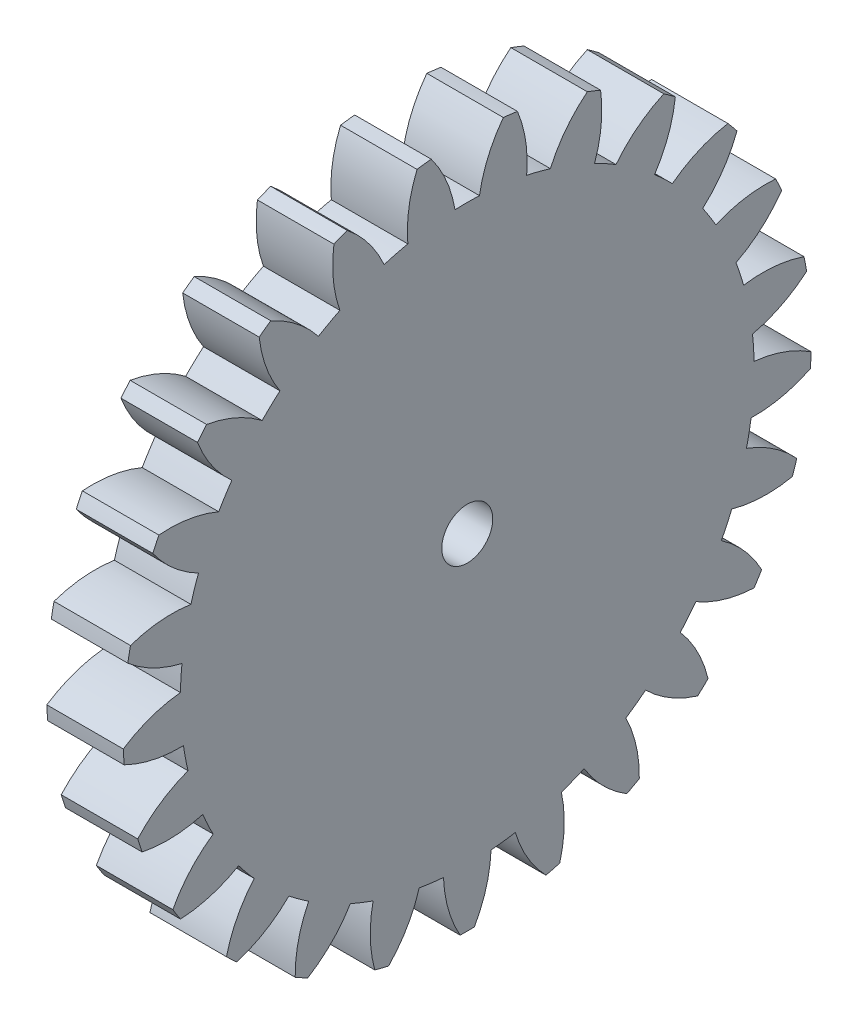
SolidWorks part; units mm, degrees
ref_plane "Plane1" through (0, 0, 0) normal (0, 0, 1) x (1, 0, 0)
ref_plane "Plane2" through (0, 0, 0) normal (0, 1, 0) x (1, 0, 0)
ref_plane "Plane3" through (0, 0, 0) normal (1, 0, 0) x (0, 0, -1)
sketch "HoldingSke" plane through (0, 0, 0) normal (0, 1, 0) x (1, 0, 0)
  line L0 (0, 0) -> (0.9063, -0.4226)
  line L1 (-15, 0) -> (100, 0) construction
  line L2 (0, 0) -> (-2.1039, 2.3779)
  line L3 (0, 0) -> (-11.863, 4.5341)
  line L4 (0, 0) -> (7.8269, 3.6497)
  line L5 (0, 0) -> (-46.8476, -17.4728)
  line L6 (0, 0) -> (-2.4869, -1.6779)
  line L7 (-2.1039, 2.3779) -> (8.6586, 51.2059)
  line L8 (-76.2, 54.61) -> (-75.9, 54.61)
  line L9 (-71.009, 38.7566) -> (-53.1078, 45.2721)
  line L10 (-76.2, 71.12) -> (104.1128, 71.12)
  line L11 (0, 0) -> (-3, 0)
  line L12 (-76.2, 101.6) -> (-76.162, 101.6)
  line L13 (24.9733, 27.94) -> (52.9518, 28.4284)
  line L14 (24.9733, 27.94) -> (24.9743, 27.94)
  line L15 (24.9733, 27.94) -> (100.4006, 29.5858)
  line L16 (-63.627, -1) -> (-12.827, -1)
  circle A0 centre (0, 0) radius 1
  circle A1 centre (0, 0) radius 11.249
  circle A2 centre (0, 0) radius 37.5
  circle A3 centre (0, 0) radius 1
  dimension "MHD" = 22.498
  dimension "Hub_dia" = 75
  dimension "Bore" = 2
  dimension "MBD" = 2
  dimension "Num_teeth" = 25
  dimension "Pitch" = 1
  dimension "Overall_len" = 50
  dimension "Show_teeth" = 25
  dimension "Thickness" = 3
  dimension "OAL" = 50.0001
  dimension "T_dim" = 0.3
  dimension "Ap" = 20
  dimension "H" = 19.05
  dimension "Pitch_radius" = 180.3128
  dimension "Width" = 3
  dimension "Backlash" = 0.038
  dimension "Addendum_fac" = 1
  dimension "Dedendum_fac" = 1.25
  dimension "Clearance_fac" = 0.25
  dimension "Dedendum_add" = 0.001
  dimension "Module" = 1
sketch "BasProSke" plane through (0, 0, 0) normal (0, 1, 0) x (1, 0, 0)
  line L0 (-10, 0) -> (60, 0) construction
  line L1 (0, 0) -> (0, 13.5)
  line L2 (0, 0) -> (3, 0)
  line L3 (3, 0) -> (3, 13.5)
  line L4 (3, 13.5) -> (0, 13.5)
  dimension "Thickness" = 3
  dimension "Diameter" = 27
revolve "Base-Revolve" add sketch "BasProSke" angle 360 about L0
sketch "TooCutSke" plane through (0, 0, 0) normal (1, 0, 0) x (0, 0, -1)
  line L1 (0, 0) -> (0, 107) construction
  line L2 (0, 0) -> (-0.8514, 12.471) construction
  line L3 (0, 0) -> (-3.1282, 24.7619) construction
  line L4 (-0.8514, 12.471) -> (-1.5641, 12.3809) construction
  arc A0 (0.4801, 11.2388) -> (-0.4801, 11.2388) centre (0, 0) ccw
  arc A1 (1.4322, 13.4494) -> (-1.4322, 13.4494) centre (0, 0) ccw
  circle A2 centre (0, 0) radius 12.5 construction
  circle A3 centre (0, 0) radius 11.7462 construction
  arc A4 (-0.4801, 11.2388) -> (-1.4322, 13.4494) centre (-5.4133, 10.4244) ccw
  arc A5 (1.4322, 13.4494) -> (0.4801, 11.2388) centre (5.4133, 10.4244) ccw
  dimension "Root_dia" = 22.498
  dimension "Overcut_dia" = 27.0508
  dimension "Pitch_dia" = 25
  dimension "Base_dia" = 23.4923
  dimension "Flank_rad" = 5
  dimension "Half_ang" = 7.2
  dimension "Half_CT" = 0.7184
extrude "ToothCut" cut sketch "TooCutSke" along normal through all
fillet "Breaks" [suppressed] radius 0.02
fillet "RootFillets" [suppressed] radius 0.251
pattern_circular "TeethCuts" count 25 every 14.4 about axis through (-10, 0, 0) along (1, 0, 0) of "ToothCut", "RootFillets", "Breaks"
sketch "HubNeaOneSke" plane through (0, 0, 0) normal (-1, 0, 0) x (0, 0, 1)
  circle A0 centre (0, 0) radius 11.249
  dimension "Diameter" = 22.498
extrude "HubNearOne" [suppressed] add sketch "HubNeaOneSke" along normal blind 47.0001
sketch "HubNeaBotSke" plane through (0, 0, 0) normal (-1, 0, 0) x (0, 0, 1)
  circle A0 centre (0, 0) radius 11.249
  dimension "Diameter" = 22.498
extrude "HubNearBoth" [suppressed] add sketch "HubNeaBotSke" along normal blind 23.5
ref_plane "FarPln" through (3, 0, 0) normal (1, 0, 0) x (0, 0, -1)
sketch "HubFarSke" plane through (3, 0, 0) normal (1, 0, 0) x (0, 0, -1)
  circle A0 centre (0, 0) radius 11.249
  dimension "Diameter" = 22.498
extrude "HubFar" [suppressed] add sketch "HubFarSke" along normal blind 23.5
sketch "BorSke" plane through (0, 0, 0) normal (1, 0, 0) x (0, 0, -1)
  circle A0 centre (0, 0) radius 1
  dimension "Diameter" = 2
extrude "Bore" cut sketch "BorSke" along normal mid plane 100.0001
sketch "KeySke" plane through (0, 0, 0) normal (1, 0, 0) x (0, 0, -1)
  line L0 (-0.4, 0) -> (-0.4, 1.3)
  line L1 (-0.4, 1.3) -> (0.4, 1.3)
  line L2 (0.4, 1.3) -> (0.4, 0)
  line L3 (0, 0) -> (0, 34) construction
  line L4 (-0.4, 0) -> (0.4, 0)
  dimension "Offset" = 1.3
  dimension "Width" = 0.8
extrude "Keyway" [suppressed] cut sketch "KeySke" along normal mid plane 100.0001
pattern_circular "Keyway2" [suppressed] count 2 every 90 about axis through (-10, 0, 0) along (1, 0, 0)
equation "' \"Module@HoldingSke\" = 6.35"
equation "' \"Num_teeth@HoldingSke\" = 12"
equation "' \"Ap@HoldingSke\" =  20"
equation "' \"Ap@HoldingSke\" = 20"
equation "' \"Width@HoldingSke\" = 0.5 * 25.4"
equation "' \"Hub_dia@HoldingSke\"= 1 * 25.4"
equation "' \"Hub_dia@HoldingSke\" = 1 * 25.4"
equation "' \"Overall_len@HoldingSke\" = 1.0 * 25.4"
equation "' \"Bore@HoldingSke\" = 0.75 * 25.4"
equation "' \"T_dim@HoldingSke\" = 0.1 * 25.4"
equation "' \"Width@KeySke\" = 0.25 * 25.4"
equation "' \"Show_teeth@HoldingSke\" = 13"
equation "' \"Backlash@HoldingSke\" = 0.009 * 25.4"
equation "' \"Addendum_fac@HoldingSke\" = 1.0"
equation "' \"Dedendum_fac@HoldingSke\" = 1.25"
equation "' \"Dedendum_add@HoldingSke\" = 0.00005 * 25.4"
equation "' \"Clearance_fac@HoldingSke\" = 0.25"
equation "\"Pitch@HoldingSke\" = 1 / \"Module@HoldingSke\""
equation "\"Overcut_dia@TooCutSke\" = (\"Num_teeth@HoldingSke\" + 2 * \"Addendum_fac@HoldingSke\") / \"Pitch@HoldingSke\" + 0.002 * 25.4"
equation "\"Pitch_dia@TooCutSke\" = \"Num_teeth@HoldingSke\" / \"Pitch@HoldingSke\""
equation "\"Base_dia@TooCutSke\" = \"Num_teeth@HoldingSke\" / \"Pitch@HoldingSke\" * cos((\"Ap@HoldingSke\"  * 3.14159265 / 180))"
equation "\"Root_dia@TooCutSke\" = (\"Num_teeth@HoldingSke\" + 2) / \"Pitch@HoldingSke\" - 2 * (\"Addendum_fac@HoldingSke\" + \"Dedendum_fac@HoldingSke\") / \"Pitch@HoldingSke\" - \"Dedendum_add@HoldingSke\" * 2"
equation "\"Half_ang@TooCutSke\" = 180 / \"Num_teeth@HoldingSke\""
equation "\"Half_CT@TooCutSke\" = \"Num_teeth@HoldingSke\" / \"Pitch@HoldingSke\" * sin((3.14159265 / 2 / \"Num_teeth@HoldingSke\")) / 2 - 7 * \"Backlash@HoldingSke\" / 4"
equation "\"Flank_rad@TooCutSke\" = \"Num_teeth@HoldingSke\" / \"Pitch@HoldingSke\" / 5"
equation "\"Radius@RootFillets\" = \"Clearance_fac@HoldingSke\" / \"Pitch@HoldingSke\" + \"Dedendum_add@HoldingSke\""
equation "\"Break_rad@Breaks\" = 0.02 / \"Pitch@HoldingSke\""
equation "\"Thickness@HoldingSke\" = \"Width@HoldingSke\""
equation "\"OAL@HoldingSke\" = \"Thickness@HoldingSke\""
equation "\"MHD@HoldingSke\" = (\"Num_teeth@HoldingSke\" + 2) / \"Pitch@HoldingSke\" - 2 * (\"Addendum_fac@HoldingSke\" + \"Dedendum_fac@HoldingSke\")  / \"Pitch@HoldingSke\" - \"Dedendum_add@HoldingSke\" * 2"
equation "\"MBD@HoldingSke\" = (\"Num_teeth@HoldingSke\" + 2) / \"Pitch@HoldingSke\" - 2 * (\"Addendum_fac@HoldingSke\" + \"Dedendum_fac@HoldingSke\")  / \"Pitch@HoldingSke\" - \"Dedendum_add@HoldingSke\" * 2 - 0.002 * 25.4"
equation "\"MHD@HoldingSke\" = ((sgn( \"MHD@HoldingSke\" - \"Hub_dia@HoldingSke\" )-1)*( \"MHD@HoldingSke\" - \"Hub_dia@HoldingSke\" ))/-2+ \"Hub_dia@HoldingSke\""
equation "\"MBD@HoldingSke\" = ((sgn( \"MBD@HoldingSke\" - \"Bore@HoldingSke\" )-1)*( \"MBD@HoldingSke\" - \"Bore@HoldingSke\" ))/-2+ \"Bore@HoldingSke\""
equation "\"OAL@HoldingSke\" = ((sgn( \"OAL@HoldingSke\" - \"Overall_len@HoldingSke\" )+1)*( \"OAL@HoldingSke\" - \"Overall_len@HoldingSke\" ))/2 + \"Overall_len@HoldingSke\" + 0.000002 * 25.4"
equation "\"Num_teeth@TeethCuts\" = int( \"Show_teeth@HoldingSke\" ) + 1"
equation "\"Num_teeth@TeethCuts\" = ((sgn( \"Num_teeth@TeethCuts\" - \"Num_teeth@HoldingSke\" )-1)*( \"Num_teeth@TeethCuts\" - \"Num_teeth@HoldingSke\" ))/-2+ \"Num_teeth@HoldingSke\""
equation "\"Num_teeth@TeethCuts\" = ((sgn( \"Num_teeth@TeethCuts\" - 2.0)+1)*( \"Num_teeth@TeethCuts\" - 2.0))/2 +2.0"
equation "\"Angle@TeethCuts\" = 360.0 / \"Num_teeth@HoldingSke\""
equation "\"Diameter@BasProSke\" = (\"Num_teeth@HoldingSke\" + 2 * \"Addendum_fac@HoldingSke\") / \"Pitch@HoldingSke\""
equation "\"Thickness@BasProSke\"  = \"Thickness@HoldingSke\""
equation "' \"Fillet_rad@BasProSke\" =  \"Thickness@HoldingSke\" * 0.05"
equation "' \"Fillet_rad@BasProSke\" = \"Thickness@HoldingSke\" * 0.05"
equation "\"MHD@HoldingSke\" = ((sgn( \"MHD@HoldingSke\" - \"Root_dia@TooCutSke\" )-1)*( \"MHD@HoldingSke\" - \"Root_dia@TooCutSke\" ))/-2+ \"Root_dia@TooCutSke\""
equation "\"Diameter@HubNeaOneSke\" = \"MHD@HoldingSke\""
equation "\"Length@HubNearOne\" = \"OAL@HoldingSke\" - \"Thickness@BasProSke\""
equation "\"Diameter@HubNeaBotSke\" = \"MHD@HoldingSke\""
equation "\"Length@HubNearBoth\" = ( \"OAL@HoldingSke\" - \"Thickness@BasProSke\" ) / 2.0"
equation "\"Thickness@FarPln\" = \"Thickness@BasProSke\""
equation "\"Diameter@HubFarSke\" = \"MHD@HoldingSke\""
equation "\"Length@HubFar\" = ( \"OAL@HoldingSke\" - \"Thickness@BasProSke\" ) / 2.0"
equation "\"Diameter@BorSke\" = \"MBD@HoldingSke\""
equation "\"D1@Bore\" = \"OAL@HoldingSke\" * 2.0"
equation "\"D1@Keyway\" = \"OAL@HoldingSke\" * 2.0"
equation "\"Offset@KeySke\" = \"T_dim@HoldingSke\" + \"MBD@HoldingSke\" / 2.0"
